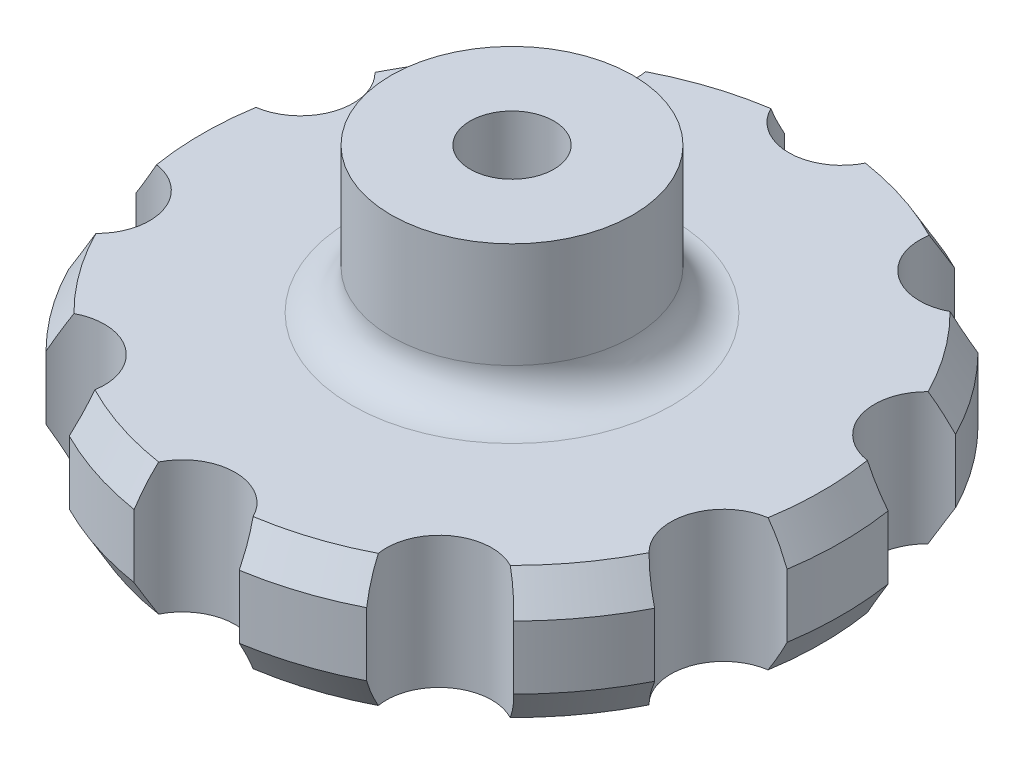
SolidWorks part; units mm, degrees
ref_plane "Front Plane" through (0, 0, 0) normal (0, 0, 1) x (1, 0, 0)
ref_plane "Top Plane" through (0, 0, 0) normal (0, 1, 0) x (1, 0, 0)
ref_plane "Right Plane" through (0, 0, 0) normal (1, 0, 0) x (0, 0, -1)
sketch "Sketch1" plane through (0, 0, 0) normal (0, 0, 1) x (1, 0, 0)
  line L0 (0, 0) -> (0, 18.0885) construction
  line L1 (3.175, 0) -> (3.175, 21)
  line L2 (3.175, 21) -> (9.175, 21)
  line L3 (9.175, 21) -> (9.175, 13)
  line L4 (12.175, 10) -> (25, 10)
  line L5 (25, 10) -> (25, 0)
  line L6 (25, 0) -> (3.175, 0)
  arc A0 (9.175, 13) -> (12.175, 10) centre (12.175, 13) ccw
  dimension "D3" = 3
  dimension "D1" = 50
  dimension "D2" = 10
  dimension "D4" = 8
  dimension "D5" = 6
  dimension "D6" = 6.35
revolve "Revolve1" add sketch "Sketch1" angle 360 about L0
sketch "Sketch4" plane through (0, 10, 0) normal (0, 1, 0) x (1, 0, 0)
  arc A0 (-3.9872, 24.68) -> (3.9872, 24.68) centre (0, 25) ccw
  circle A1 centre (0, 0) radius 25 construction
  arc A2 (3.9872, 24.68) -> (-3.9872, 24.68) centre (0, 0) ccw
  dimension "D1" = 4
extrude "Cut-Extrude3" cut sketch "Sketch4" against normal through all
chamfer "Chamfer1" distance 1.5 angle 60 2 edges at (0, 0, 25) (0, 10, 25)
pattern_circular "CirPattern1" count 10 over 360 about axis through (0, 0, 0) along (0, 1, 0) of "Cut-Extrude3"
sketch "Sketch3" plane through (0, 0, 0) normal (0, -1, 0) x (1, 0, 0)
  line L1 (3.2079, 5.5562) -> (-3.2079, 5.5562)
  line L2 (-3.2079, 5.5562) -> (-6.4158, 0)
  line L3 (-6.4158, 0) -> (-3.2079, -5.5562)
  line L4 (-3.2079, -5.5562) -> (3.2079, -5.5562)
  line L5 (3.2079, -5.5562) -> (6.4158, 0)
  line L6 (6.4158, 0) -> (3.2079, 5.5562)
  circle A0 centre (0, 0) radius 5.5563 construction
  dimension "D1" = 11.1125
extrude "Cut-Extrude2" cut sketch "Sketch3" against normal blind 5
